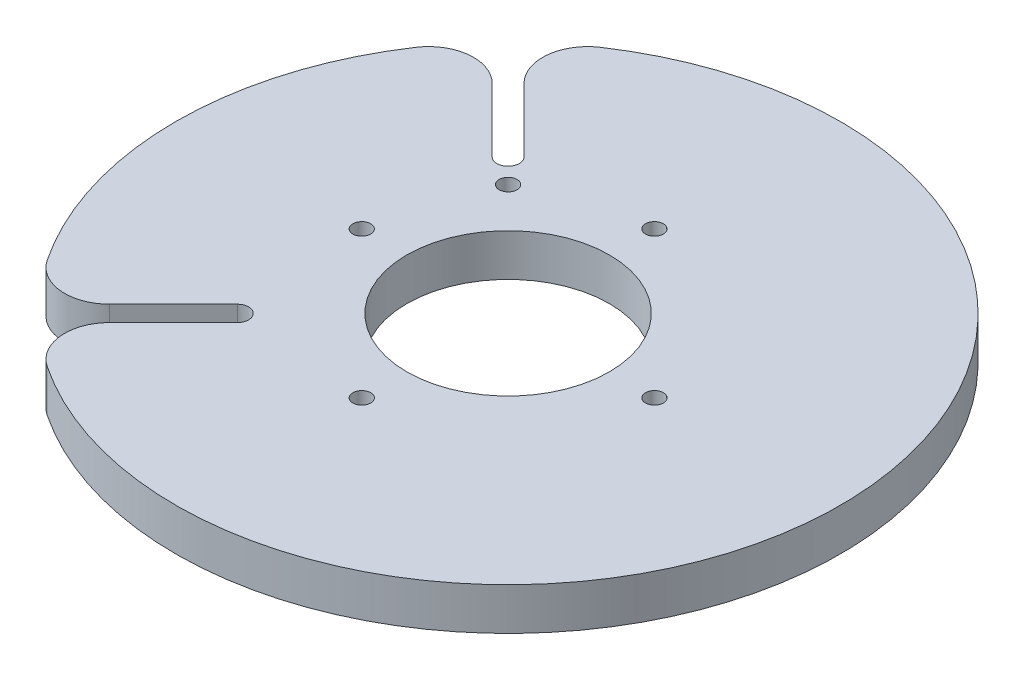
SolidWorks part; units mm, degrees
ref_plane "Front" through (0, 0, 0) normal (0, 0, 1) x (1, 0, 0)
ref_plane "Top" through (0, 0, 0) normal (0, 1, 0) x (1, 0, 0)
ref_plane "Right" through (0, 0, 0) normal (1, 0, 0) x (0, 0, -1)
sketch "Sketch1" plane through (0, 0, 0) normal (0, 1, 0) x (1, 0, 0)
  circle A0 centre (0, 0) radius 75
  dimension "D1" = 150
extrude "Boss-Extrude1" add sketch "Sketch1" along normal blind 9.525
sketch "Sketch2" plane through (0, 9.525, 0) normal (0, 1, 0) x (1, 0, 0)
  circle A0 centre (0, 0) radius 22.098
  dimension "D1" = 44.196
extrude "Cut-Extrude1" [suppressed] cut sketch "Sketch2" against normal through all
hole_wizard "M3 Clearance Hole1" [suppressed] positions "Sketch4" profile "Sketch5" hole size "M3" standard "ANSI Metric"
sketch "Sketch4" plane through (0, 6.35, 0) normal (0, 1, 0) x (1, 0, 0)
  circle A0 centre (0, 0) radius 27 construction
  point P0 (-27, 0)
  point P4 (0, 27)
  point P6 (27, 0)
  point P8 (0, -27)
  dimension "D1" = 54
sketch "Sketch5" plane through (-27, 6.35, 0) normal (1, 0, 0) x (0, 0, 1)
  line L0 (0, 0) -> (0, 6.35)
  line L1 (0, 6.35) -> (1.7, 6.35)
  line L2 (1.7, 6.35) -> (1.7, 0)
  line L5 (1.7, 0) -> (0, 0)
  line L11 (0, -6.35) -> (0, 107.95) construction
  dimension "Thru Hole Dia." = 3.4
  dimension "Thru Hole Depth" = 6.35
hole_wizard "M3 Clearance Slot1" [suppressed] positions "Sketch7" profile "Sketch6" size "M3" standard "ANSI Metric"
sketch "Sketch7" plane through (0, 0, 0) normal (0, -1, 0) x (-1, 0, 0)
  line L0 (55, -30) -> (25, -30) construction
  line L1 (0, 0) -> (52.8466, 0) construction
  arc A1 (53.3, -31.7) -> (53.3, -28.3) centre (53.3, -30) ccw construction
  arc A2 (26.7, -28.3) -> (26.7, -31.7) centre (26.7, -30) ccw construction
  point P0 (40, -30)
sketch "Sketch6" plane through (-40, 0, 30) normal (1, 0, 0) x (0, 0, -1)
  line L0 (0, 0) -> (0, 26.4215)
  line L1 (0, 26.4215) -> (1.7, 25.4)
  line L2 (1.7, 25.4) -> (1.7, 0)
  line L5 (1.7, 0) -> (0, 0)
  line L10 (0, 26.4215) -> (-1.7, 25.4) construction
  line L11 (0, -6.35) -> (0, 107.95) construction
  dimension "Hole Dia." = 3.4
  dimension "Hole Depth" = 25.4
  dimension "Drill Angle" = 118
hole_wizard "M3 Clearance Hole2" [suppressed] positions "Sketch9" profile "Sketch8" hole size "M3" standard "ANSI Metric"
sketch "Sketch9" plane through (0, 6.35, 0) normal (0, 1, 0) x (1, 0, 0)
  point P0 (-53.3, 30)
sketch "Sketch8" plane through (-53.3, 6.35, -30) normal (1, 0, 0) x (0, 0, 1)
  line L0 (0, 0) -> (0, 6.35)
  line L1 (0, 6.35) -> (1.7, 6.35)
  line L2 (1.7, 6.35) -> (1.7, 0)
  line L5 (1.7, 0) -> (0, 0)
  line L11 (0, -6.35) -> (0, 107.95) construction
  dimension "Thru Hole Dia." = 3.4
  dimension "Thru Hole Depth" = 6.35
sketch "Sketch11" plane through (0, 9.525, 0) normal (0, 1, 0) x (1, 0, 0)
  line L0 (-75, 0) -> (75, 0) construction
  line L1 (0, 0) -> (-53.033, 53.033) construction
  line L2 (-54.7986, 51.2065) -> (-32.348, 28.7559)
  line L3 (-51.2065, 54.7986) -> (-28.7559, 32.348)
  line L4 (-51.2065, -54.7986) -> (-28.7559, -32.348)
  line L5 (-54.7986, -51.2065) -> (-32.348, -28.7559)
  circle A0 centre (0, 0) radius 75 construction
  arc A1 (-32.348, 28.7559) -> (-28.7559, 32.348) centre (-30.5519, 30.5519) ccw
  arc A2 (-32.348, -28.7559) -> (-28.7559, -32.348) centre (-30.5519, -30.5519) cw
  arc A3 (-54.7986, 51.2065) -> (-51.2065, 54.7986) centre (0, 0) cw
  arc A4 (-54.7986, -51.2065) -> (-51.2065, -54.7986) centre (0, 0) ccw
  dimension "D1" = 45
  dimension "D2" = 31.75
  dimension "D3" = 5.08
extrude "Cut-Extrude2" cut sketch "Sketch11" against normal up to next
fillet "Fillet1" radius 10.16 4 edges at (-51.2065, 4.7625, 54.7986) (-54.7986, 4.7625, 51.2065) (-54.7986, 4.7625, -51.2065) (-51.2065, 4.7625, -54.7986)
extrude "Cut-Extrude26" [suppressed] cut sketch "Sketch35" against normal through all
sketch "Sketch35" plane through (-73.7688, 9.525, -121.0804) normal (0, 1, 0) x (1, 0, 0)
  circle A1 centre (48.605, -95.9166) radius 2.0193 construction
  circle A3 centre (73.7688, -121.0804) radius 22.86 construction
  circle A4 centre (73.7688, -121.0804) radius 35.587 construction
  arc A5 (40.7129, -134.2614) -> (42.8303, -138.6656) centre (73.7688, -121.0804) ccw construction
  arc A6 (33.7184, -137.0504) -> (36.2838, -142.3866) centre (73.7688, -121.0804) ccw
  arc A7 (47.7074, -131.4723) -> (49.3768, -134.9446) centre (73.7688, -121.0804) ccw
  arc A8 (47.7074, -131.4723) -> (33.7184, -137.0504) centre (40.7129, -134.2614) ccw
  arc A9 (36.2838, -142.3866) -> (49.3768, -134.9446) centre (42.8303, -138.6656) ccw
  point P9 (41.6959, -136.4999)
extrude "Cut-Extrude30" cut sketch "Sketch39" against normal through all
sketch "Sketch39" plane through (-73.7688, 9.525, -121.0804) normal (0, 1, 0) x (1, 0, 0)
  line L0 (73.7688, -121.0804) -> (73.7688, -88.0604) construction
  circle A1 centre (73.7688, -121.0804) radius 77.46 construction
  circle A2 centre (73.7688, -121.0804) radius 22.86
  circle A3 centre (73.7688, -88.0604) radius 2.0193
  circle A4 centre (106.7888, -121.0804) radius 2.0193
  circle A5 centre (73.7688, -154.1004) radius 2.0193
  circle A6 centre (40.7488, -121.0804) radius 2.0193
  point P4 (73.7688, -98.2204)
  point P16 (73.7688, -121.0804)
extrude "Cut-Extrude33" cut sketch "Sketch42" against normal through all
sketch "Sketch42" plane through (-73.7688, 9.525, -121.0804) normal (0, 1, 0) x (1, 0, 0)
  line L0 (43.2169, -90.5284) -> (48.605, -95.9166) construction
  arc A1 (41.4208, -92.3245) -> (45.0129, -88.7324) centre (43.2169, -90.5284) ccw construction
  circle A2 centre (48.605, -95.9166) radius 2.0193
extrude "Cut-Extrude35" [suppressed] cut sketch "Sketch44" against normal through all
sketch "Sketch44" plane through (-73.7688, 9.525, -121.0804) normal (0, 1, 0) x (1, 0, 0)
  circle A2 centre (73.7688, -121.0804) radius 22.86 construction
  circle A3 centre (48.605, -95.9166) radius 2.0193 construction
  circle A4 centre (73.7688, -121.0804) radius 35.587 construction
  arc A5 (40.5263, -133.7834) -> (43.5223, -139.8309) centre (73.7688, -121.0804) ccw construction
  arc A6 (34.406, -136.1222) -> (37.9536, -143.283) centre (73.7688, -121.0804) ccw
  arc A7 (46.6466, -131.4446) -> (49.091, -136.3787) centre (73.7688, -121.0804) ccw
  arc A8 (46.6466, -131.4446) -> (34.406, -136.1222) centre (40.5263, -133.7834) ccw
  arc A9 (37.9536, -143.283) -> (49.091, -136.3787) centre (43.5223, -139.8309) ccw
  point P9 (41.8806, -136.8783)
